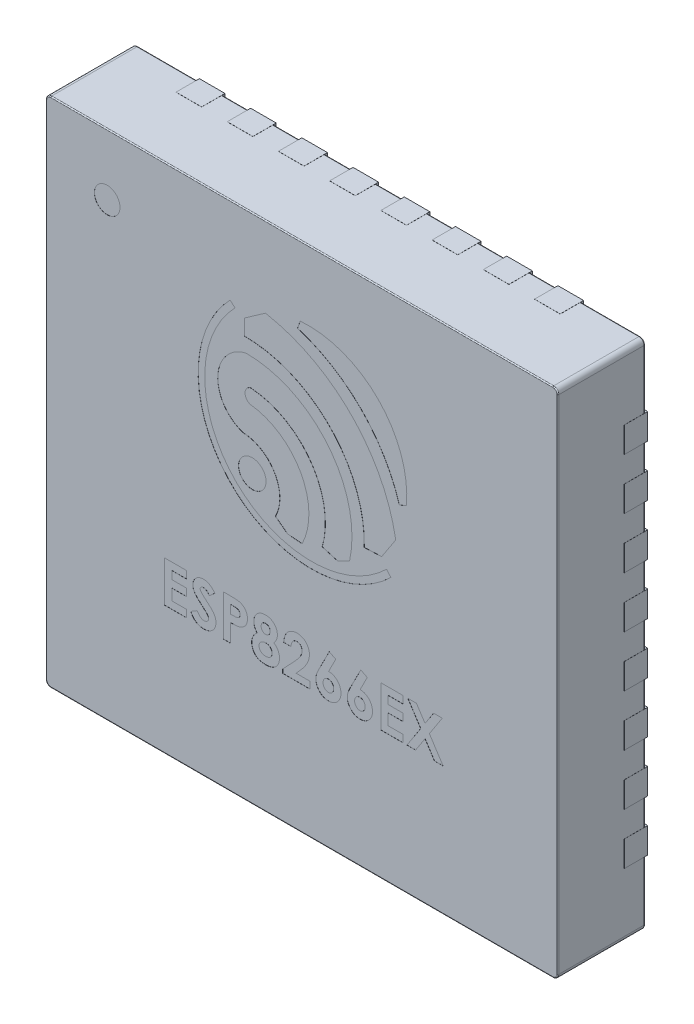
SolidWorks part; units mm, degrees
other "ESP8266EX-SoC" parameters "D5"=0.3678, "D1"=3.1308, "D2"=3.0402, "D3"=0.4115, "D4"=0.3, "D6"=0.3296, "D7"=0.2637, "D8"=0.9806, "D10"=0.5, "D11"=0.25, "D9"=4
ref_plane "Front Plane" through (0, 0, 0) normal (0, 0, 1) x (1, 0, 0)
ref_plane "Top Plane" through (0, 0, 0) normal (0, 1, 0) x (1, 0, 0)
ref_plane "Right Plane" through (0, 0, 0) normal (1, 0, 0) x (0, 0, -1)
sketch "Sketch1" plane through (0, 0, 0) normal (0, 1, 0) x (1, 0, 0)
  line L1 (-2.5, -2.5) -> (2.5, -2.5)
  line L2 (-2.5, -2.5) -> (-2.5, 2.5)
  line L3 (-2.5, 2.5) -> (2.5, 2.5)
  line L4 (2.5, -2.5) -> (2.5, 2.5)
  line L5 (-2.5, -2.5) -> (2.5, 2.5) construction
  line L6 (-2.5, 2.5) -> (2.5, -2.5) construction
  point P0 (0, 0)
  dimension "D1" = 5
  dimension "D2" = 5
extrude "Boss-Extrude1" add sketch "Sketch1" along normal blind 0.85
fillet "Fillet1" radius 0.05 4 edges at (2.5, 0.425, -2.5) (2.5, 0.425, 2.5) (-2.5, 0.425, 2.5) (-2.5, 0.425, -2.5)
fillet "Fillet2" radius 0.01 16 edges at (2.4854, 0.85, 2.4854) (0, 0.85, 2.5) (-2.4854, 0.85, 2.4854) (-2.5, 0.85, 0) (-2.4854, 0.85, -2.4854) (0, 0.85, -2.5) (2.4854, 0.85, -2.4854) (2.5, 0.85, 0) (2.5, 0, 0) (2.4854, 0, -2.4854) (0, 0, -2.5) (2.4854, 0, 2.4854) (0, 0, 2.5) (-2.4854, 0, 2.4854) (-2.5, 0, 0) (-2.4854, 0, -2.4854)
sketch "Sketch2" plane through (0, 0, 0) normal (0, -1, 0) x (1, 0, 0)
  line L0 (1.55, 1.85) -> (1.85, 1.55)
  line L1 (-1.8, -1.85) -> (1.8, -1.85)
  line L2 (-1.85, -1.8) -> (-1.85, 1.8)
  line L3 (-1.8, 1.85) -> (1.55, 1.85)
  line L4 (1.85, -1.8) -> (1.85, 1.55)
  line L5 (-1.8354, -1.8354) -> (1.85, 1.85) construction
  line L6 (-1.8354, 1.8354) -> (1.8354, -1.8354) construction
  line L7 (1.55, 1.85) -> (1.85, 1.85) construction
  line L8 (1.85, 1.55) -> (1.85, 1.85) construction
  line L9 (-1.85, 1.85) -> (-1.8, 1.85) construction
  line L10 (-1.85, 1.85) -> (-1.8354, 1.8354) construction
  line L11 (-1.85, 1.8) -> (-1.85, 1.85) construction
  line L12 (-1.85, -1.85) -> (-1.85, -1.8) construction
  line L13 (-1.85, -1.85) -> (-1.8354, -1.8354) construction
  line L14 (-1.85, -1.85) -> (-1.8, -1.85) construction
  line L15 (1.85, -1.85) -> (1.85, -1.8) construction
  line L16 (1.8354, -1.8354) -> (1.85, -1.85) construction
  line L17 (1.8, -1.85) -> (1.85, -1.85) construction
  line L18 (0, -1000) -> (0, 49000) construction
  line L23 (-0.375, 2.501) -> (-0.125, 2.501)
  line L24 (-0.375, 2.501) -> (-0.375, 2.101)
  line L25 (-0.375, 2.101) -> (-0.125, 2.101)
  line L26 (-0.125, 2.501) -> (-0.125, 2.101)
  line L27 (-0.375, 2.501) -> (-0.125, 2.101) construction
  line L28 (-0.375, 2.101) -> (-0.125, 2.501) construction
  line L30 (-0.875, 2.501) -> (-0.875, 2.101)
  line L31 (-0.875, 2.501) -> (-0.625, 2.501)
  line L32 (-0.625, 2.501) -> (-0.625, 2.101)
  line L33 (-0.875, 2.101) -> (-0.625, 2.101)
  line L34 (-0.875, 2.101) -> (-0.625, 2.501) construction
  line L35 (-0.875, 2.501) -> (-0.625, 2.101) construction
  line L36 (-1.375, 2.501) -> (-1.375, 2.101)
  line L37 (-1.375, 2.501) -> (-1.125, 2.501)
  line L38 (-1.125, 2.501) -> (-1.125, 2.101)
  line L39 (-1.375, 2.101) -> (-1.125, 2.101)
  line L40 (-1.375, 2.101) -> (-1.125, 2.501) construction
  line L41 (-1.375, 2.501) -> (-1.125, 2.101) construction
  line L42 (-1.875, 2.501) -> (-1.875, 2.101)
  line L43 (-1.875, 2.501) -> (-1.625, 2.501)
  line L44 (-1.625, 2.501) -> (-1.625, 2.101)
  line L45 (-1.875, 2.101) -> (-1.625, 2.101)
  line L46 (-1.875, 2.101) -> (-1.625, 2.501) construction
  line L47 (-1.875, 2.501) -> (-1.625, 2.101) construction
  line L48 (-0.375, 2.501) -> (-0.875, 2.501) construction
  line L162 (-1000, 0) -> (49000, 0) construction
  line L163 (-2.5, 2.5) -> (2.5, 2.5) construction
  line L164 (0.375, 2.501) -> (0.875, 2.501) construction
  line L165 (1.875, 2.501) -> (1.625, 2.101) construction
  line L166 (1.875, 2.101) -> (1.625, 2.501) construction
  line L167 (1.375, 2.501) -> (1.125, 2.101) construction
  line L168 (1.375, 2.101) -> (1.125, 2.501) construction
  line L169 (0.875, 2.501) -> (0.625, 2.101) construction
  line L170 (0.875, 2.101) -> (0.625, 2.501) construction
  line L171 (0.375, 2.101) -> (0.125, 2.501) construction
  line L172 (0.375, 2.501) -> (0.125, 2.101) construction
  line L173 (1.875, 2.101) -> (1.625, 2.101)
  line L174 (1.625, 2.501) -> (1.625, 2.101)
  line L175 (1.875, 2.501) -> (1.625, 2.501)
  line L176 (1.875, 2.501) -> (1.875, 2.101)
  line L177 (1.375, 2.101) -> (1.125, 2.101)
  line L178 (1.125, 2.501) -> (1.125, 2.101)
  line L179 (1.375, 2.501) -> (1.125, 2.501)
  line L180 (1.375, 2.501) -> (1.375, 2.101)
  line L181 (0.875, 2.101) -> (0.625, 2.101)
  line L182 (0.625, 2.501) -> (0.625, 2.101)
  line L183 (0.875, 2.501) -> (0.625, 2.501)
  line L184 (0.875, 2.501) -> (0.875, 2.101)
  line L185 (0.125, 2.501) -> (0.125, 2.101)
  line L186 (0.375, 2.101) -> (0.125, 2.101)
  line L187 (0.375, 2.501) -> (0.375, 2.101)
  line L188 (0.375, 2.501) -> (0.125, 2.501)
  line L189 (0.375, -2.501) -> (0.125, -2.101) construction
  line L190 (0.375, -2.101) -> (0.125, -2.501) construction
  line L191 (0.875, -2.101) -> (0.625, -2.501) construction
  line L192 (0.875, -2.501) -> (0.625, -2.101) construction
  line L193 (1.375, -2.101) -> (1.125, -2.501) construction
  line L194 (1.375, -2.501) -> (1.125, -2.101) construction
  line L195 (1.875, -2.101) -> (1.625, -2.501) construction
  line L196 (1.875, -2.501) -> (1.625, -2.101) construction
  line L197 (0.375, -2.501) -> (0.875, -2.501) construction
  line L198 (-0.375, -2.501) -> (-0.875, -2.501) construction
  line L199 (-1.875, -2.501) -> (-1.625, -2.101) construction
  line L200 (-1.875, -2.101) -> (-1.625, -2.501) construction
  line L201 (-1.375, -2.501) -> (-1.125, -2.101) construction
  line L202 (-1.375, -2.101) -> (-1.125, -2.501) construction
  line L203 (-0.875, -2.501) -> (-0.625, -2.101) construction
  line L204 (-0.875, -2.101) -> (-0.625, -2.501) construction
  line L205 (-0.375, -2.101) -> (-0.125, -2.501) construction
  line L206 (-0.375, -2.501) -> (-0.125, -2.101) construction
  line L207 (0.375, -2.501) -> (0.125, -2.501)
  line L208 (0.375, -2.501) -> (0.375, -2.101)
  line L209 (0.375, -2.101) -> (0.125, -2.101)
  line L210 (0.125, -2.501) -> (0.125, -2.101)
  line L211 (0.875, -2.501) -> (0.875, -2.101)
  line L212 (0.875, -2.501) -> (0.625, -2.501)
  line L213 (0.625, -2.501) -> (0.625, -2.101)
  line L214 (0.875, -2.101) -> (0.625, -2.101)
  line L215 (1.375, -2.501) -> (1.375, -2.101)
  line L216 (1.375, -2.501) -> (1.125, -2.501)
  line L217 (1.125, -2.501) -> (1.125, -2.101)
  line L218 (1.375, -2.101) -> (1.125, -2.101)
  line L219 (1.875, -2.501) -> (1.875, -2.101)
  line L220 (1.875, -2.501) -> (1.625, -2.501)
  line L221 (1.625, -2.501) -> (1.625, -2.101)
  line L222 (1.875, -2.101) -> (1.625, -2.101)
  line L223 (-1.875, -2.101) -> (-1.625, -2.101)
  line L224 (-1.625, -2.501) -> (-1.625, -2.101)
  line L225 (-1.875, -2.501) -> (-1.625, -2.501)
  line L226 (-1.875, -2.501) -> (-1.875, -2.101)
  line L227 (-1.375, -2.101) -> (-1.125, -2.101)
  line L228 (-1.125, -2.501) -> (-1.125, -2.101)
  line L229 (-1.375, -2.501) -> (-1.125, -2.501)
  line L230 (-1.375, -2.501) -> (-1.375, -2.101)
  line L231 (-0.875, -2.101) -> (-0.625, -2.101)
  line L232 (-0.625, -2.501) -> (-0.625, -2.101)
  line L233 (-0.875, -2.501) -> (-0.625, -2.501)
  line L234 (-0.875, -2.501) -> (-0.875, -2.101)
  line L235 (-0.125, -2.501) -> (-0.125, -2.101)
  line L236 (-0.375, -2.101) -> (-0.125, -2.101)
  line L237 (-0.375, -2.501) -> (-0.375, -2.101)
  line L238 (-0.375, -2.501) -> (-0.125, -2.501)
  line L239 (2.501, 0.375) -> (2.101, 0.125) construction
  line L240 (2.101, 0.375) -> (2.501, 0.125) construction
  line L241 (2.101, 0.875) -> (2.501, 0.625) construction
  line L242 (2.501, 0.875) -> (2.101, 0.625) construction
  line L243 (2.101, 1.375) -> (2.501, 1.125) construction
  line L244 (2.501, 1.375) -> (2.101, 1.125) construction
  line L245 (2.101, 1.875) -> (2.501, 1.625) construction
  line L246 (2.501, 1.875) -> (2.101, 1.625) construction
  line L247 (2.501, 0.375) -> (2.501, 0.875) construction
  line L248 (2.501, -0.375) -> (2.501, -0.875) construction
  line L249 (2.501, -1.875) -> (2.101, -1.625) construction
  line L250 (2.101, -1.875) -> (2.501, -1.625) construction
  line L251 (2.501, -1.375) -> (2.101, -1.125) construction
  line L252 (2.101, -1.375) -> (2.501, -1.125) construction
  line L253 (2.501, -0.875) -> (2.101, -0.625) construction
  line L254 (2.101, -0.875) -> (2.501, -0.625) construction
  line L255 (2.101, -0.375) -> (2.501, -0.125) construction
  line L256 (2.501, -0.375) -> (2.101, -0.125) construction
  line L257 (2.501, 0.375) -> (2.501, 0.125)
  line L258 (2.501, 0.375) -> (2.101, 0.375)
  line L259 (2.101, 0.375) -> (2.101, 0.125)
  line L260 (2.501, 0.125) -> (2.101, 0.125)
  line L261 (2.501, 0.875) -> (2.101, 0.875)
  line L262 (2.501, 0.875) -> (2.501, 0.625)
  line L263 (2.501, 0.625) -> (2.101, 0.625)
  line L264 (2.101, 0.875) -> (2.101, 0.625)
  line L265 (2.501, 1.375) -> (2.101, 1.375)
  line L266 (2.501, 1.375) -> (2.501, 1.125)
  line L267 (2.501, 1.125) -> (2.101, 1.125)
  line L268 (2.101, 1.375) -> (2.101, 1.125)
  line L269 (2.501, 1.875) -> (2.101, 1.875)
  line L270 (2.501, 1.875) -> (2.501, 1.625)
  line L271 (2.501, 1.625) -> (2.101, 1.625)
  line L272 (2.101, 1.875) -> (2.101, 1.625)
  line L273 (2.101, -1.875) -> (2.101, -1.625)
  line L274 (2.501, -1.625) -> (2.101, -1.625)
  line L275 (2.501, -1.875) -> (2.501, -1.625)
  line L276 (2.501, -1.875) -> (2.101, -1.875)
  line L277 (2.101, -1.375) -> (2.101, -1.125)
  line L278 (2.501, -1.125) -> (2.101, -1.125)
  line L279 (2.501, -1.375) -> (2.501, -1.125)
  line L280 (2.501, -1.375) -> (2.101, -1.375)
  line L281 (2.101, -0.875) -> (2.101, -0.625)
  line L282 (2.501, -0.625) -> (2.101, -0.625)
  line L283 (2.501, -0.875) -> (2.501, -0.625)
  line L284 (2.501, -0.875) -> (2.101, -0.875)
  line L285 (2.501, -0.125) -> (2.101, -0.125)
  line L286 (2.101, -0.375) -> (2.101, -0.125)
  line L287 (2.501, -0.375) -> (2.101, -0.375)
  line L288 (2.501, -0.375) -> (2.501, -0.125)
  line L289 (-2.501, -0.375) -> (-2.101, -0.125) construction
  line L290 (-2.101, -0.375) -> (-2.501, -0.125) construction
  line L291 (-2.101, -0.875) -> (-2.501, -0.625) construction
  line L292 (-2.501, -0.875) -> (-2.101, -0.625) construction
  line L293 (-2.101, -1.375) -> (-2.501, -1.125) construction
  line L294 (-2.501, -1.375) -> (-2.101, -1.125) construction
  line L295 (-2.101, -1.875) -> (-2.501, -1.625) construction
  line L296 (-2.501, -1.875) -> (-2.101, -1.625) construction
  line L297 (-2.501, -0.375) -> (-2.501, -0.875) construction
  line L298 (-2.501, 0.375) -> (-2.501, 0.875) construction
  line L299 (-2.501, 1.875) -> (-2.101, 1.625) construction
  line L300 (-2.101, 1.875) -> (-2.501, 1.625) construction
  line L301 (-2.501, 1.375) -> (-2.101, 1.125) construction
  line L302 (-2.101, 1.375) -> (-2.501, 1.125) construction
  line L303 (-2.501, 0.875) -> (-2.101, 0.625) construction
  line L304 (-2.101, 0.875) -> (-2.501, 0.625) construction
  line L305 (-2.101, 0.375) -> (-2.501, 0.125) construction
  line L306 (-2.501, 0.375) -> (-2.101, 0.125) construction
  line L307 (-2.501, -0.375) -> (-2.501, -0.125)
  line L308 (-2.501, -0.375) -> (-2.101, -0.375)
  line L309 (-2.101, -0.375) -> (-2.101, -0.125)
  line L310 (-2.501, -0.125) -> (-2.101, -0.125)
  line L311 (-2.501, -0.875) -> (-2.101, -0.875)
  line L312 (-2.501, -0.875) -> (-2.501, -0.625)
  line L313 (-2.501, -0.625) -> (-2.101, -0.625)
  line L314 (-2.101, -0.875) -> (-2.101, -0.625)
  line L315 (-2.501, -1.375) -> (-2.101, -1.375)
  line L316 (-2.501, -1.375) -> (-2.501, -1.125)
  line L317 (-2.501, -1.125) -> (-2.101, -1.125)
  line L318 (-2.101, -1.375) -> (-2.101, -1.125)
  line L319 (-2.501, -1.875) -> (-2.101, -1.875)
  line L320 (-2.501, -1.875) -> (-2.501, -1.625)
  line L321 (-2.501, -1.625) -> (-2.101, -1.625)
  line L322 (-2.101, -1.875) -> (-2.101, -1.625)
  line L323 (-2.101, 1.875) -> (-2.101, 1.625)
  line L324 (-2.501, 1.625) -> (-2.101, 1.625)
  line L325 (-2.501, 1.875) -> (-2.501, 1.625)
  line L326 (-2.501, 1.875) -> (-2.101, 1.875)
  line L327 (-2.101, 1.375) -> (-2.101, 1.125)
  line L328 (-2.501, 1.125) -> (-2.101, 1.125)
  line L329 (-2.501, 1.375) -> (-2.501, 1.125)
  line L330 (-2.501, 1.375) -> (-2.101, 1.375)
  line L331 (-2.101, 0.875) -> (-2.101, 0.625)
  line L332 (-2.501, 0.625) -> (-2.101, 0.625)
  line L333 (-2.501, 0.875) -> (-2.501, 0.625)
  line L334 (-2.501, 0.875) -> (-2.101, 0.875)
  line L335 (-2.501, 0.125) -> (-2.101, 0.125)
  line L336 (-2.101, 0.375) -> (-2.101, 0.125)
  line L337 (-2.501, 0.375) -> (-2.101, 0.375)
  line L338 (-2.501, 0.375) -> (-2.501, 0.125)
  arc A0 (-1.8, 1.85) -> (-1.85, 1.8) centre (-1.8, 1.8) ccw
  arc A1 (-1.85, -1.8) -> (-1.8, -1.85) centre (-1.8, -1.8) ccw
  arc A2 (1.8, -1.85) -> (1.85, -1.8) centre (1.8, -1.8) ccw
  point P0 (0, 0)
  point P12 (-0.25, 2.301)
  point P60 (0.25, 2.301)
  point P93 (0.25, -2.301)
  point P94 (-0.25, -2.301)
  point P127 (2.301, 0.25)
  point P128 (2.301, -0.25)
  point P161 (-2.301, -0.25)
  point P162 (-2.301, 0.25)
  dimension "D5" = 0.1
  dimension "D1" = 3.7
  dimension "D2" = 3.7
  dimension "D4" = 45
  dimension "D6" = 0.4
  dimension "D7" = 0.25
  dimension "D8" = 0.25
  dimension "D11" = 0.001
  dimension "D3" = 0.3
extrude "Boss-Extrude2" add sketch "Sketch2" along normal blind 0.025 and the other way blind 0.203
sketch "Sketch3" plane through (0, 0.85, 0) normal (0, 1, 0) x (1, 0, 0)
  line L7 (-2.5, 1.245) -> (2.5, 1.245) construction
  line L8 (-2.5, 2.5) -> (-2.5, -2.5) construction
  line L9 (2.45, -2.5) -> (-2.45, -2.5) construction
  line L11 (2.5, 2.45) -> (2.5, -2.45) construction
  line L12 (-0.9518, -0.7471) -> (-1.0208, -0.7765)
  line L13 (0.0158, -1.8185) -> (0.0421, -1.7451)
  line L14 (-0.6089, -0.2172) -> (-0.779, -0.2245)
  line L15 (-0.779, -0.2245) -> (-0.9165, -0.4344)
  line L16 (0.3554, -1.7159) -> (0.5618, -1.5711)
  line L17 (0.5618, -1.5711) -> (0.5618, -1.419)
  line L18 (0.6522, -1.6116) -> (0.7003, -1.6542)
  line L19 (-0.8697, -0.0941) -> (-0.8269, -0.142)
  line L20 (0.2577, -0.0472) -> (0.1393, 0.0424)
  line L21 (0.1393, 0.0424) -> (-0.0028, 0.0549)
  line L22 (-0.199, -0.0176) -> (-0.3492, 0.0271)
  line L23 (-0.3492, 0.0271) -> (-0.4663, -0.0315)
  line L24 (0, 0) -> (0, 2.49) construction
  line L25 (2.45, 2.49) -> (-2.45, 2.49) construction
  circle A10 centre (1.9, -1.9) radius 0.125
  arc A11 (-0.9518, -0.7471) -> (0.0421, -1.7451) centre (0.4836, -0.3116) ccw
  arc A12 (-0.9165, -0.4344) -> (0.3554, -1.7159) centre (0.6355, -0.1661) ccw
  arc A13 (0.5445, -1.2833) -> (0.574, -0.5963) centre (0.4641, -0.9357) ccw
  arc A14 (0.7003, -1.6542) -> (-0.8697, -0.0941) centre (-0.0948, -0.8843) ccw
  circle A15 centre (0.4836, -0.295) radius 0.1343
  arc A16 (-0.199, -0.0176) -> (0.5015, -1.0117) centre (0.551, -0.233) ccw
  arc A17 (0.2577, -0.0472) -> (0.574, -0.5963) centre (0.5901, -0.2214) ccw
  arc A18 (-0.0028, 0.0549) -> (0.5041, -0.8706) centre (0.5757, -0.2299) ccw
  arc A19 (-0.4663, -0.0315) -> (0.5445, -1.2833) centre (0.5449, -0.249) ccw
  arc A20 (0.6522, -1.6116) -> (-0.8269, -0.142) centre (-0.0948, -0.8843) ccw
  arc A21 (-0.6089, -0.2172) -> (0.5618, -1.419) centre (0.5606, -0.2491) ccw
  arc A22 (0.5041, -0.8706) -> (0.5015, -1.0117) centre (0.4804, -0.9407) cw
  arc A23 (-1.0208, -0.7765) -> (0.0158, -1.8185) centre (-0.0638, -0.861) ccw
  text T0 "ESP8266EX" font "Century Gothic" height 0.4
  point P0 (0, 1.245)
  point P52 (0, 0)
  dimension "D2" = 0.25
  dimension "D3" = 0.6
  dimension "D4" = 0.6
extrude "Cut-Extrude1" cut sketch "Sketch3" against normal blind 0.001
move or copy body "Body-Move/Copy1" bodies to move or copy 131 copy no rotation origin (0, 0, 0) rotation axis (0, 0.7071, 0.7071) rotation angle 180
move or copy body "Body-Move/Copy2" bodies to move or copy 132 copy no translate (0, 0, 0.025)
equation "\"D8@Sketch2\"=\"D10@Sketch2\"/2"
equation "\"D4@Sketch3\"=\"D3@Sketch3\""
